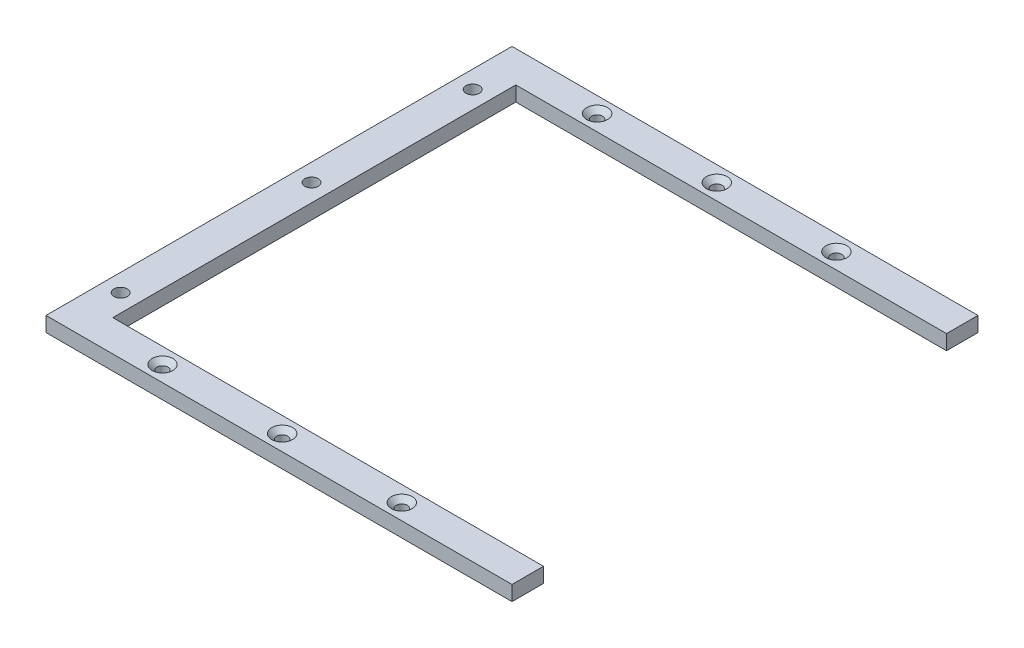
SolidWorks part; units mm, degrees
material "6061 Alloy"
ref_plane "Front Plane" through (0, 0, 0) normal (0, 0, 1) x (1, 0, 0)
ref_plane "Top Plane" through (0, 0, 0) normal (0, 1, 0) x (1, 0, 0)
ref_plane "Right Plane" through (0, 0, 0) normal (1, 0, 0) x (0, 0, -1)
sketch "Sketch1" plane through (0, 0, 1.58) normal (0, -1, 0) x (1, 0, 0)
  line L88 (93.98, -1.58) -> (93.98, 92.4) construction
  line L89 (93.98, 92.4) -> (0, 92.4) construction
  line L90 (0, 92.4) -> (0, -1.58) construction
  line L91 (0, -1.58) -> (93.98, -1.58) construction
  circle A0 centre (3.56, 80.91) radius 1.7 construction
  circle A1 centre (20.32, 89.225) radius 1.1 construction
  circle A12 centre (30.4, 80.4) radius 1.35 construction
  circle A13 centre (44.45, 89.225) radius 1.1 construction
  circle A82 centre (68.58, 89.225) radius 1.1 construction
  circle A122 centre (88.11, 60.84) radius 1.75 construction
  circle A123 centre (79.3, 55.35) radius 1.35 construction
  circle A132 centre (3.56, 42.41) radius 1.7 construction
  circle A159 centre (3.56, 9.91) radius 1.7 construction
  circle A160 centre (20.32, 1.575) radius 1.1 construction
  circle A167 centre (44.45, 1.575) radius 1.1 construction
  circle A178 centre (68.58, 1.575) radius 1.1 construction
  circle A179 centre (90, 10.4) radius 1.35 construction
  dimension "D7" = 2.2
  dimension "D11" = 3.4
  dimension "D12" = 2.7
  dimension "D13" = 3.5
  dimension "D14" = 2.7
  dimension "D15" = 2.7
  dimension "D16" = 43.99
  dimension "D17" = 32.5
  dimension "D1" = 3.56
  dimension "D2" = 20.32
  dimension "D3" = 30.4
  dimension "D4" = 24.13
  dimension "D5" = 24.13
  dimension "D6" = 3.175
  dimension "D8" = 93.98
  dimension "D9" = 93.98
  dimension "D10" = 3.155
  dimension "D18" = 38.5
  dimension "D19" = 12
  dimension "D20" = 5.87
  dimension "D21" = 31.56
  dimension "D22" = 14.68
  dimension "D23" = 37.05
  dimension "D24" = 3.98
  dimension "D25" = 11.98
other "AlignGroup1"
other "AlignGroup2"
other "AlignGroup3"
other "AlignGroup4"
other "AlignGroup5"
other "AlignGroup6"
sketch "Sketch2" plane through (0, 0, 0) normal (0, 1, 0) x (1, 0, 0)
  line L0 (93.98, 0) -> (93.98, -93.98) construction
  line L1 (0, -93.98) -> (93.98, -93.98)
  line L2 (0, -93.98) -> (0, -87.63)
  line L3 (0, -87.63) -> (93.98, -87.63)
  line L4 (93.98, -93.98) -> (93.98, -87.63)
  line L5 (0, -6.35) -> (0, -87.63)
  line L6 (0, 0) -> (93.98, 0)
  line L7 (0, 0) -> (0, -6.35)
  line L8 (0, -6.35) -> (93.98, -6.35)
  line L9 (93.98, 0) -> (93.98, -6.35)
  line L10 (0, -43.99) -> (7.12, -43.99) construction
  line L11 (0, -87.63) -> (7.12, -87.63)
  line L12 (0, -87.63) -> (0, -6.35)
  line L13 (0, -6.35) -> (7.12, -6.35)
  line L14 (7.12, -87.63) -> (7.12, -6.35)
  line L15 (93.98, -93.98) -> (93.98, 0)
  line L16 (93.98, -93.98) -> (101.1, -93.98)
  line L17 (93.98, 0) -> (101.1, 0)
  line L18 (101.1, -93.98) -> (101.1, 0)
  line L19 (20.32, -87.63) -> (20.32, -93.98) construction
  circle A0 centre (20.32, -90.805) radius 1.1
  circle A1 centre (44.45, -90.805) radius 1.1
  circle A2 centre (68.58, -90.805) radius 1.1
  circle A3 centre (20.32, -3.155) radius 1.1
  circle A4 centre (44.45, -3.155) radius 1.1
  circle A5 centre (68.58, -3.155) radius 1.1
  circle A6 centre (3.56, -82.49) radius 1.35
  circle A7 centre (3.56, -43.99) radius 1.35
  circle A8 centre (3.56, -11.49) radius 1.35
  point P14 (20.32, -90.805)
  point P37 (3.56, -43.99)
  point P47 (20.32, -90.805)
  point P48 (0, 0)
  dimension "D1" = 2.2
  dimension "D2" = 2.7
extrude "Boss-Extrude1" add sketch "Sketch2" along normal blind 3 contours L3 L14 L8 L5 A8 A7 A6 | L9 L6 L7 L8 A5 A4 A3 | L1 L4 L3 L2 A2 A1 A0
chamfer "Chamfer1" distance 1 angle 45 6 edges at (68.58, 3, 91.905) (44.45, 3, 91.905) (44.45, 3, 4.255) (68.58, 3, 4.255) (20.32, 3, 4.255) (20.32, 3, 91.905)
